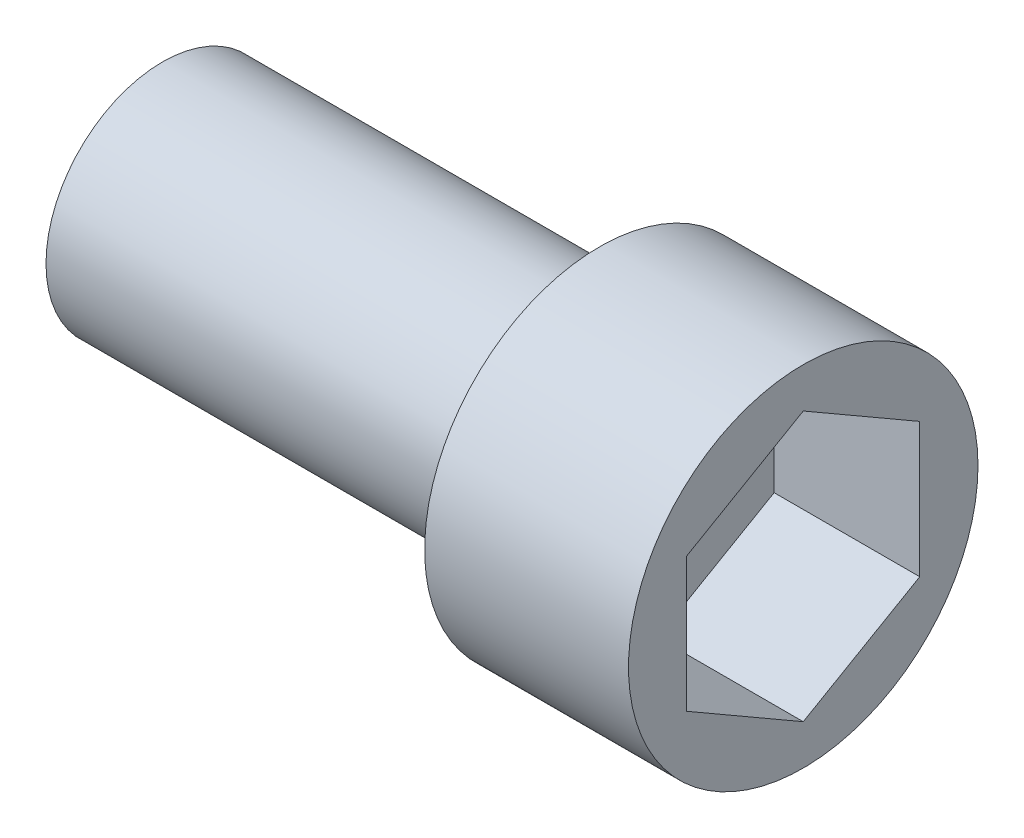
SolidWorks part; units mm, degrees
ref_plane "Front Plane" through (0, 0, 0) normal (1, 0, 0) x (0, 1, 0)
ref_plane "Top Plane" through (0, 0, 0) normal (0, 0, 1) x (0, 1, 0)
ref_plane "Right Plane" through (0, 0, 0) normal (0, 1, 0) x (-1, 0, 0)
sketch "Sketch1" plane through (0, 0, 0) normal (1, 0, 0) x (0, 1, 0)
  circle A0 centre (0, 0) radius 6
  dimension "D1" = 12
extrude "Boss-Extrude1" add sketch "Sketch1" along normal blind 7
sketch "Sketch2" plane through (7, 0, 0) normal (1, 0, 0) x (0, 1, 0)
  line L1 (4.6188, 0) -> (2.3094, 4)
  line L2 (2.3094, 4) -> (-2.3094, 4)
  line L3 (-2.3094, 4) -> (-4.6188, 0)
  line L4 (-4.6188, 0) -> (-2.3094, -4)
  line L5 (-2.3094, -4) -> (2.3094, -4)
  line L6 (2.3094, -4) -> (4.6188, 0)
  circle A0 centre (0, 0) radius 4 construction
  dimension "D1" = 8
extrude "Cut-Extrude1" cut sketch "Sketch2" against normal blind 5
sketch "Sketch3" plane through (0, 0, 0) normal (-1, 0, 0) x (0, -1, 0)
  circle A0 centre (0, 0) radius 4
  dimension "D1" = 8
extrude "Boss-Extrude2" add sketch "Sketch3" along normal blind 15
